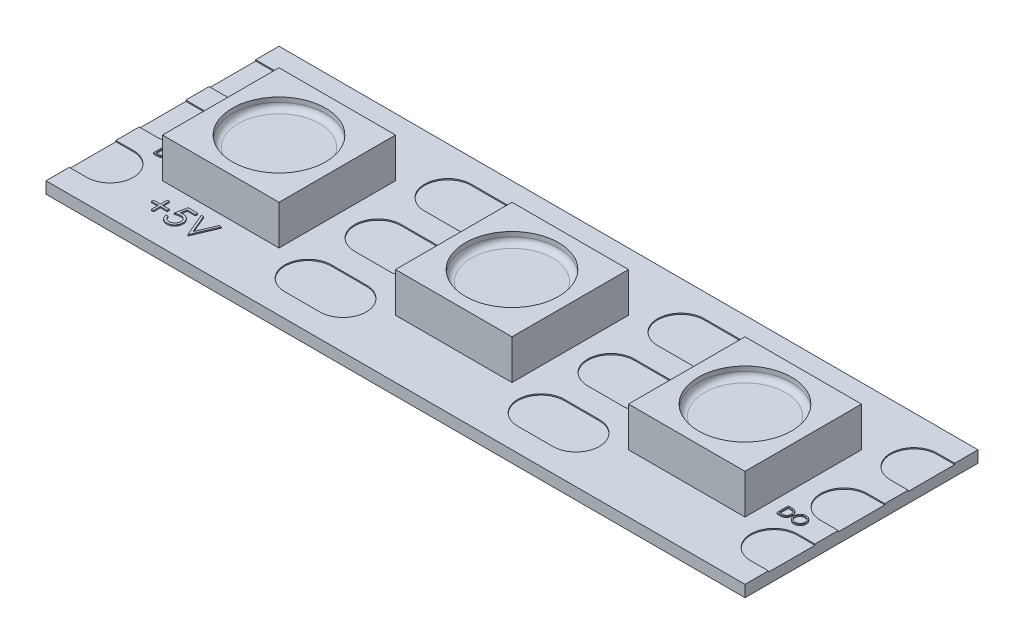
SolidWorks part; units mm, degrees
ref_plane "Front Plane" through (0, 0, 0) normal (0, 0, 1) x (1, 0, 0)
ref_plane "Top Plane" through (0, 0, 0) normal (0, 1, 0) x (1, 0, 0)
ref_plane "Right Plane" through (0, 0, 0) normal (1, 0, 0) x (0, 0, -1)
sketch "Sketch1" plane through (0, 0, 0) normal (0, 1, 0) x (1, 0, 0)
  line L1 (-15, 5) -> (15, 5)
  line L2 (-15, 5) -> (-15, -5)
  line L3 (-15, -5) -> (15, -5)
  line L4 (15, 5) -> (15, -5)
  line L5 (0, -5) -> (0, 5) construction
  line L6 (-15, 0) -> (15, 0) construction
  point P0 (0, 0)
  dimension "D1" = 30
  dimension "D2" = 10
extrude "base Strip" add sketch "Sketch1" along normal blind 0.5
sketch "Sketch2" plane through (0, 0.5, 0) normal (0, 1, 0) x (1, 0, 0)
  line L0 (-15, 0) -> (15, 0) construction
  line L1 (-15, 5) -> (-15, -5) construction
  line L2 (15, -5) -> (15, 5) construction
  line L3 (12.5, -2.5) -> (7.5, -2.5)
  line L4 (15, 5) -> (-15, 5) construction
  line L5 (0, -5) -> (0, 5) construction
  line L6 (-15, -5) -> (15, -5) construction
  line L7 (-2.5, 2.5) -> (2.5, 2.5)
  line L8 (-2.5, 2.5) -> (-2.5, -2.5)
  line L9 (-2.5, -2.5) -> (2.5, -2.5)
  line L10 (2.5, 2.5) -> (2.5, -2.5)
  line L11 (0, -2.5) -> (0, 2.5) construction
  line L12 (-2.5, 0) -> (2.5, 0) construction
  line L13 (-12.5, 2.5) -> (-7.5, 2.5)
  line L14 (-12.5, 2.5) -> (-12.5, -2.5)
  line L15 (-12.5, -2.5) -> (-7.5, -2.5)
  line L16 (-7.5, 2.5) -> (-7.5, -2.5)
  line L17 (-10, -2.5) -> (-10, 2.5) construction
  line L18 (-12.5, 0) -> (-7.5, 0) construction
  line L19 (7.5, 2.5) -> (7.5, -2.5)
  line L20 (12.5, 2.5) -> (7.5, 2.5)
  line L21 (12.5, 2.5) -> (12.5, -2.5)
  point P7 (0, 0)
  point P16 (-10, 0)
  dimension "D1" = 5
  dimension "D2" = 5
  dimension "D3" = 10
extrude "Neopixels" add sketch "Sketch2" along normal blind 1.7
sketch "Sketch3" plane through (0, 2.2, 0) normal (0, 1, 0) x (1, 0, 0)
  line L0 (-10, 2.5) -> (-10, -2.5) construction
  line L1 (-7.5, 2.5) -> (-12.5, 2.5) construction
  line L2 (-12.5, -2.5) -> (-7.5, -2.5) construction
  circle A0 centre (-10, 0) radius 2
  circle A1 centre (0, 0) radius 2
  circle A2 centre (10, 0) radius 2
  dimension "D1" = 4
  dimension "D2" = 3
extrude "neopixel lens" cut sketch "Sketch3" against normal blind 0.45
fillet "Fillet1" radius 0.25 3 edges at (10, 1.75, 2) (0, 1.75, 2) (-10, 1.75, 2)
sketch "Sketch4" plane through (0, 1.75, 0) normal (0, 1, 0) x (1, 0, 0)
  point P0 (-10, 0)
  point P1 (0, 0)
  point P3 (10, 0)
sketch "Sketch5" plane through (0, 0.5, 0) normal (0, 1, 0) x (1, 0, 0)
  line L0 (-5, 5) -> (-5, -5) construction
  line L1 (15, 5) -> (-15, 5) construction
  line L2 (-15, -5) -> (15, -5) construction
  line L3 (5, 5) -> (5, -5) construction
  line L4 (-15, 0) -> (15, 0) construction
  line L5 (-15, 5) -> (-15, -5) construction
  line L6 (15, -5) -> (15, 5) construction
  line L7 (-5.75, 3) -> (-4.25, 3) construction
  line L8 (-5.75, 4) -> (-4.25, 4)
  line L9 (-5.75, 2) -> (-4.25, 2)
  line L10 (-5.75, -3) -> (-4.25, -3) construction
  line L11 (-5.75, -4) -> (-4.25, -4)
  line L12 (-5.75, -2) -> (-4.25, -2)
  line L13 (-5.75, 0) -> (-4.25, 0) construction
  line L14 (-5.75, 1) -> (-4.25, 1)
  line L15 (-5.75, -1) -> (-4.25, -1)
  line L16 (0, -1000) -> (0, 49000) construction
  line L17 (5.75, -3) -> (4.25, -3) construction
  line L18 (5.75, -4) -> (4.25, -4)
  line L19 (5.75, -2) -> (4.25, -2)
  line L20 (5.75, 0) -> (4.25, 0) construction
  line L21 (5.75, 1) -> (4.25, 1)
  line L22 (5.75, -1) -> (4.25, -1)
  line L23 (5.75, 3) -> (4.25, 3) construction
  line L24 (5.75, 4) -> (4.25, 4)
  line L25 (5.75, 2) -> (4.25, 2)
  line L26 (15, 4) -> (14.25, 4)
  line L27 (15, 2) -> (14.25, 2)
  line L28 (15, 1) -> (14.25, 1)
  line L29 (15, -1) -> (14.25, -1)
  line L30 (15, -4) -> (14.25, -4)
  line L31 (15, -2) -> (14.25, -2)
  line L32 (15.75, -3) -> (14.25, -3) construction
  line L33 (15.75, 0) -> (14.25, 0) construction
  line L34 (15.75, 3) -> (14.25, 3) construction
  line L35 (-15.75, -3) -> (-14.25, -3) construction
  line L36 (-15, -4) -> (-14.25, -4)
  line L37 (-15, -2) -> (-14.25, -2)
  line L38 (-15.75, 0) -> (-14.25, 0) construction
  line L39 (-15, 1) -> (-14.25, 1)
  line L40 (-15, -1) -> (-14.25, -1)
  line L41 (-15.75, 3) -> (-14.25, 3) construction
  line L42 (-15, 4) -> (-14.25, 4)
  line L43 (-15, 2) -> (-14.25, 2)
  line L44 (-15, 2) -> (-15, 4)
  line L45 (-15, -1) -> (-15, 1)
  line L46 (-15, -4) -> (-15, -2)
  line L47 (15, 4) -> (15, 2)
  line L48 (15, 1) -> (15, -1)
  line L49 (15, -2) -> (15, -4)
  arc A0 (-5.75, 4) -> (-5.75, 2) centre (-5.75, 3) ccw
  arc A1 (-4.25, 2) -> (-4.25, 4) centre (-4.25, 3) ccw
  arc A2 (-5.75, -4) -> (-5.75, -2) centre (-5.75, -3) cw
  arc A3 (-4.25, -2) -> (-4.25, -4) centre (-4.25, -3) cw
  arc A4 (-5.75, 1) -> (-5.75, -1) centre (-5.75, 0) ccw
  arc A5 (-4.25, -1) -> (-4.25, 1) centre (-4.25, 0) ccw
  arc A6 (5.75, -4) -> (5.75, -2) centre (5.75, -3) ccw
  arc A7 (4.25, -2) -> (4.25, -4) centre (4.25, -3) ccw
  arc A8 (5.75, 1) -> (5.75, -1) centre (5.75, 0) cw
  arc A9 (4.25, -1) -> (4.25, 1) centre (4.25, 0) cw
  arc A10 (5.75, 4) -> (5.75, 2) centre (5.75, 3) cw
  arc A11 (4.25, 2) -> (4.25, 4) centre (4.25, 3) cw
  arc A12 (14.25, 2) -> (14.25, 4) centre (14.25, 3) cw
  arc A14 (14.25, -1) -> (14.25, 1) centre (14.25, 0) cw
  arc A16 (14.25, -2) -> (14.25, -4) centre (14.25, -3) ccw
  arc A19 (-14.25, -2) -> (-14.25, -4) centre (-14.25, -3) cw
  arc A21 (-14.25, -1) -> (-14.25, 1) centre (-14.25, 0) ccw
  arc A23 (-14.25, 2) -> (-14.25, 4) centre (-14.25, 3) ccw
  arc A24 (15.75, 4) -> (15.75, 2) centre (15.75, 3) cw [skipped]
  arc A25 (15.75, 1) -> (15.75, -1) centre (15.75, 0) cw [skipped]
  arc A26 (15.75, -4) -> (15.75, -2) centre (15.75, -3) ccw [skipped]
  point P17 (-5, 3)
  point P22 (-6.75, 3)
  point P23 (-3.25, 3)
  point P26 (-5, -3)
  point P34 (-5, 0)
  point P42 (5, -3)
  point P49 (5, 0)
  point P56 (5, 3)
  point P65 (15, -3)
  point P72 (15, 0)
  point P79 (15, 3)
  point P84 (-15, -3)
  point P91 (-15, 0)
  point P98 (-15, 3)
  dimension "D4" = 1
  dimension "D1" = 10
  dimension "D2" = 5
  dimension "D3" = 3.5
  dimension "D5" = 3
  dimension "D8" = 10
  dimension "D6" = 2
  dimension "D7" = 2
extrude "Cut-Extrude1" cut sketch "Sketch5" against normal blind 0.05
sketch "Sketch6" plane through (0, 0.5, 0) normal (0, 1, 0) x (1, 0, 0)
  line L0 (-1, 3.675) -> (0.1, 3.675)
  line L1 (0.1, 3.675) -> (0.1, 4.1)
  line L2 (0.1, 4.1) -> (1, 3.5)
  line L3 (-1, 3.675) -> (-1, 3.325)
  line L4 (-1.017, 3.5) -> (2.2396, 3.5) construction
  line L5 (0.1, 2.9) -> (1, 3.5)
  line L6 (0.1, 3.325) -> (0.1, 2.9)
  line L7 (-1, 3.325) -> (0.1, 3.325)
  line L8 (0, -1000) -> (0, 49000) construction
  text T0 "GND" font "Century Gothic" height 1
  text T1 "+5V" font "Century Gothic" height 1
  text T2 "DO" font "Century Gothic" height 0.5
  text T3 "DI" font "Century Gothic" height 0.5
  point P11 (-1, 3.5)
  dimension "D1" = 1
  dimension "D2" = 2
  dimension "D3" = 0.6
  dimension "D4" = 0.9
  dimension "D5" = 3.5
  dimension "D6" = 0.35
  dimension "D7" = 12
  dimension "D8" = 3
  dimension "D9" = 4
  dimension "D10" = 1.7
  dimension "D11" = 13
  dimension "D12" = 13.75
extrude "Boss-Extrude1" add sketch "Sketch6" along normal blind 0.05
